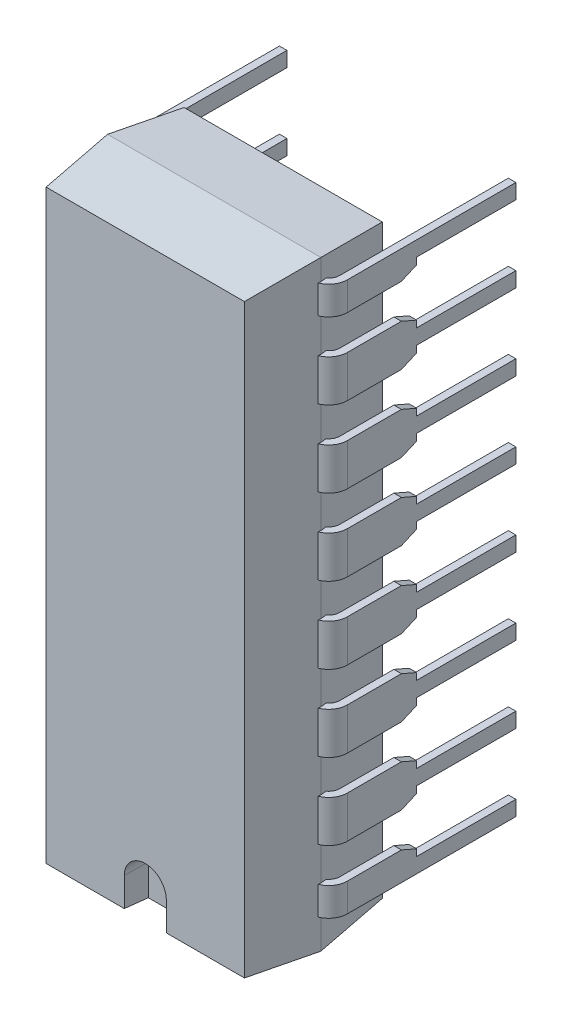
SolidWorks part; units mm, degrees
ref_plane "Plane1" through (0, 0, 0) normal (0, 0, 1) x (1, 0, 0)
ref_plane "Plane2" through (0, 0, 0) normal (0, 1, 0) x (1, 0, 0)
ref_plane "Plane3" through (0, 0, 0) normal (1, 0, 0) x (0, 0, -1)
sketch "Sketch1" plane through (0, 0, 0) normal (0, 1, 0) x (1, 0, 0)
  line L0 (-3.3, -5.1) -> (-3.55, -2.805)
  line L1 (-3.55, -2.805) -> (3.55, -2.805) construction
  line L2 (3.55, -2.805) -> (3.3, -5.1)
  line L3 (3.3, -5.1) -> (-3.3, -5.1)
  line L4 (-3.55, -2.805) -> (-3.3, -0.51)
  line L5 (-3.3, -0.51) -> (3.3, -0.51)
  line L6 (3.3, -0.51) -> (3.55, -2.805)
  line L7 (0, 0) -> (3.3, 0) construction
  line L8 (0, -0.51) -> (0, -5.1) construction
  point P11 (0, -2.805)
  point P12 (0, -5.1)
  point P13 (0, -0.51)
  dimension "D1" = 0.51
  dimension "F" = 7.1
  dimension "D2" = 5.1
  dimension "D4" = 6.6
extrude "Basic Shape" add sketch "Sketch1" along normal mid plane 20
sketch "Sketch2" plane through (0, 0, 0) normal (1, 0, 0) x (0, 0, -1)
  line L1 (-0.51, -10) -> (-2.805, -10) construction
  line L2 (-0.51, 10) -> (-0.51, -10) construction
  line L3 (-0.51, 10) -> (-0.51, 9.75)
  line L4 (-0.51, 10) -> (-2.805, 10) construction
  line L5 (-0.51, 10) -> (-2.805, 10)
  line L6 (-2.805, 10) -> (-0.51, 9.75)
  line L7 (-0.51, -10) -> (-2.805, -10)
  line L9 (-2.805, -10) -> (-0.51, -9.75)
  line L11 (-0.51, -9.75) -> (-0.51, -10)
  dimension "D1" = 0.25
extrude "Side Profile1" cut sketch "Sketch2" against normal through all and the other way through all
sketch "Sketch3" plane through (0, 0, 0) normal (1, 0, 0) x (0, 0, -1)
  line L0 (-2.805, 10) -> (-5.1, 10) construction
  line L1 (-2.805, 10) -> (-5.1, 10)
  line L2 (-5.1, 10) -> (-5.1, -10) construction
  line L3 (-5.1, 10) -> (-5.1, 9.75)
  line L4 (-2.805, 10) -> (-5.1, 9.75)
  line L5 (-2.805, -10) -> (-5.1, -10) construction
  line L6 (-2.805, -10) -> (-5.1, -10)
  line L7 (-2.805, -10) -> (-5.1, -9.75)
  line L8 (-5.1, -9.75) -> (-5.1, -10)
extrude "Side Profile2" cut sketch "Sketch3" against normal through all and the other way through all
sketch "First Pin Location" plane through (0, 0, 0) normal (1, 0, 0) x (0, 0, -1)
  line L0 (-2.805, 10) -> (-2.805, -10) construction
  point P0 (-2.805, -10)
  point P1 (-2.805, -8.73)
  dimension "Z" = 1.27
ref_plane "First Pin Plane" through (0, -8.73, 0) normal (0, 1, 0) x (-1, 0, 0)
sketch "Sketch4" plane through (0, 0, 5.1) normal (0, 0, 1) x (1, 0, 0)
  line L2 (-0.7, -10) -> (-0.7, -8.8)
  line L3 (0.7, -8.8) -> (0.7, -10)
  line L4 (-3.55, -10) -> (3.55, -10) construction
  line L5 (-0.7, -10) -> (0.7, -10)
  arc A0 (-0.7, -8.8) -> (0.7, -8.8) centre (0, -8.8) cw
  dimension "D1" = 1.2
  dimension "D2" = 1.4
extrude "Location Mark" cut sketch "Sketch4" against normal blind 0.8
sketch "Sketch5" plane through (0, -8.73, 0) normal (0, 1, 0) x (1, 0, 0)
  line L0 (-3.55, -2.805) -> (3.55, -2.805) construction
  line L1 (0, -2.805) -> (3.31, -2.805)
  line L2 (3.81, -2.305) -> (3.81, 3.3)
  line L3 (3.81, -2.805) -> (-3.81, -2.805) construction
  arc A0 (3.81, -2.305) -> (3.31, -2.805) centre (3.31, -2.305) cw
  point P0 (-3.81, -2.805)
  point P8 (0, -2.805)
  dimension "D3" = 3.3
  dimension "D2" = 0.5
  dimension "D1" = 7.62
sketch "Sketch6" plane through (0, 0, 0) normal (1, 0, 0) x (0, 0, -1)
  line L0 (-2.93, -8.035) -> (-2.68, -8.035)
  line L1 (-2.93, -8.035) -> (-2.93, -9.425)
  line L2 (-2.68, -9.425) -> (-2.93, -9.425)
  line L3 (-2.68, -9.425) -> (-2.68, -8.035)
  line L4 (-2.68, -8.035) -> (-2.93, -9.425) construction
  point P4 (-2.805, -8.73)
  dimension "D1" = 1.39
  dimension "D2" = 0.25
sweep "First Pin" add profiles "Sketch6" path "Sketch5"
sketch "Sketch7" plane through (3.685, 0, 0) normal (-1, 0, 0) x (0, 0, 1)
  line L0 (-3.3, -9.425) -> (-3.3, -8.035) construction
  line L1 (-3.3, -8.035) -> (-3.3, -9.425) construction
  line L2 (-3.3, -8.98) -> (-3.3, -8.48) construction
  line L3 (-3.3, -8.98) -> (0, -8.98)
  line L4 (0.51, 9.75) -> (0.51, -9.75) construction
  line L5 (-3.3, -8.48) -> (0, -8.48)
  line L6 (0, -8.48) -> (0, -8.2575)
  line L7 (0, -8.98) -> (0, -9.2025)
  line L8 (2.305, -8.035) -> (-3.3, -8.035) construction
  line L9 (0.51, -8.035) -> (-3.3, -8.035)
  line L10 (2.305, -9.425) -> (-3.3, -9.425) construction
  line L11 (0.51, -9.425) -> (-3.3, -9.425)
  line L12 (-3.3, -8.98) -> (-3.3, -9.425)
  line L13 (-3.3, -8.035) -> (-3.3, -8.48)
  line L14 (0, -9.2025) -> (0.51, -9.425)
  line L16 (0, -8.2575) -> (0.51, -8.035)
  point P10 (-3.3, -8.2575)
  dimension "D1" = 0.5
extrude "Pin Relief" cut sketch "Sketch7" against normal through all
mirror "Opp Pin" about plane through (0, 0, 0) normal (1, 0, 0) of "Pin Relief", "First Pin"
pattern_linear "Remaining Pins" count 8 spacing 2.54 along (0, 1, 0) of "First Pin", "Opp Pin", "Pin Relief"
sketch "Sketch9" plane through (0, -9.425, 0) normal (0, -1, 0) x (1, 0, 0)
  line L0 (3.935, 0) -> (3.685, 0) construction
  line L1 (3.935, 0) -> (3.685, 0)
  line L2 (-3.935, 0) -> (-3.685, 0) construction
  line L3 (-3.935, 0) -> (-3.685, 0)
  line L7 (3.685, 2.305) -> (3.685, 0.51)
  line L8 (3.685, 0.51) -> (3.935, 0.51)
  line L9 (3.935, 0.51) -> (3.935, 2.305)
  line L11 (3.5412, 2.8857) -> (3.55, 2.805)
  line L12 (3.55, 2.805) -> (3.5287, 2.6096)
  line L14 (3.685, 2.305) -> (3.685, 0)
  line L16 (3.935, 0) -> (3.935, 2.305)
  line L18 (3.5412, 2.8857) -> (3.55, 2.805)
  line L19 (3.55, 2.805) -> (3.5287, 2.6096)
  line L22 (-3.685, 0.51) -> (-3.685, 2.305)
  line L24 (-3.5287, 2.6096) -> (-3.55, 2.805)
  line L25 (-3.55, 2.805) -> (-3.5412, 2.8857)
  line L27 (-3.935, 2.305) -> (-3.935, 0.51)
  line L28 (-3.935, 0.51) -> (-3.685, 0.51)
  line L29 (-3.685, 0) -> (-3.685, 2.305)
  line L31 (-3.5287, 2.6096) -> (-3.55, 2.805)
  line L32 (-3.55, 2.805) -> (-3.5412, 2.8857)
  line L34 (-3.935, 2.305) -> (-3.935, 0)
  arc A2 (3.935, 2.305) -> (3.5412, 2.8857) centre (3.31, 2.305) ccw
  arc A3 (3.935, 2.305) -> (3.5412, 2.8857) centre (3.31, 2.305) ccw
  arc A4 (3.685, 2.305) -> (3.5287, 2.6096) centre (3.31, 2.305) ccw
  arc A5 (3.685, 2.305) -> (3.5287, 2.6096) centre (3.31, 2.305) ccw
  arc A6 (-3.5287, 2.6096) -> (-3.685, 2.305) centre (-3.31, 2.305) ccw
  arc A7 (-3.5287, 2.6096) -> (-3.685, 2.305) centre (-3.31, 2.305) ccw
  arc A8 (-3.5412, 2.8857) -> (-3.935, 2.305) centre (-3.31, 2.305) ccw
  arc A9 (-3.5412, 2.8857) -> (-3.935, 2.305) centre (-3.31, 2.305) ccw
  dimension "D1" = 0
  dimension "D2" = 0
extrude "Pin Relief1" cut sketch "Sketch9" against normal up to surface (0.445 mm away) up to face at (-3.81, -8.98, -1.65)
sketch "Sketch10" plane through (0, 9.745, 0) normal (0, 1, 0) x (-1, 0, 0)
  line L0 (3.935, 0) -> (3.685, 0) construction
  line L1 (3.935, 0) -> (3.685, 0)
  line L2 (-3.935, 0) -> (-3.685, 0) construction
  line L3 (-3.935, 0) -> (-3.685, 0)
  line L7 (3.685, 0.51) -> (3.935, 0.51)
  line L8 (3.935, 0.51) -> (3.935, 2.305)
  line L10 (3.5412, 2.8857) -> (3.55, 2.805)
  line L11 (3.55, 2.805) -> (3.5287, 2.6096)
  line L13 (3.685, 2.305) -> (3.685, 0.51)
  line L14 (-3.935, 0.51) -> (-3.685, 0.51)
  line L15 (3.935, 0) -> (3.935, 2.305)
  line L16 (-3.685, 0.51) -> (-3.685, 2.305)
  line L17 (3.5412, 2.8857) -> (3.55, 2.805)
  line L18 (3.55, 2.805) -> (3.5287, 2.6096)
  line L19 (-3.5287, 2.6096) -> (-3.55, 2.805)
  line L20 (3.685, 2.305) -> (3.685, 0)
  line L21 (-3.55, 2.805) -> (-3.5412, 2.8857)
  line L22 (-3.935, 2.305) -> (-3.935, 0.51)
  line L24 (-3.685, 0) -> (-3.685, 2.305)
  line L25 (-3.5287, 2.6096) -> (-3.55, 2.805)
  line L26 (-3.55, 2.805) -> (-3.5412, 2.8857)
  line L27 (-3.935, 2.305) -> (-3.935, 0)
  arc A2 (3.935, 2.305) -> (3.5412, 2.8857) centre (3.31, 2.305) ccw
  arc A3 (3.935, 2.305) -> (3.5412, 2.8857) centre (3.31, 2.305) ccw
  arc A4 (3.685, 2.305) -> (3.5287, 2.6096) centre (3.31, 2.305) ccw
  arc A5 (3.685, 2.305) -> (3.5287, 2.6096) centre (3.31, 2.305) ccw
  arc A6 (-3.5287, 2.6096) -> (-3.685, 2.305) centre (-3.31, 2.305) ccw
  arc A7 (-3.5412, 2.8857) -> (-3.935, 2.305) centre (-3.31, 2.305) ccw
  arc A8 (-3.5287, 2.6096) -> (-3.685, 2.305) centre (-3.31, 2.305) ccw
  arc A9 (-3.5412, 2.8857) -> (-3.935, 2.305) centre (-3.31, 2.305) ccw
  dimension "D1" = 0
  dimension "D2" = 0
extrude "Pin Relief2" cut sketch "Sketch10" against normal up to surface (0.445 mm away) up to face at (-3.81, 9.3, -1.65)
sketch "Component_Outline" plane through (0, 0, 0) normal (0, 0, 1) x (1, 0, 0)
  line L0 (3.55, 10) -> (3.55, 9.3)
  line L1 (3.55, 9.3) -> (3.935, 9.3)
  line L2 (3.935, 9.3) -> (3.935, 8.355)
  line L3 (3.935, 8.355) -> (3.55, 8.355)
  line L4 (3.55, 8.355) -> (3.55, 7.205)
  line L5 (3.55, 7.205) -> (3.935, 7.205)
  line L6 (3.935, 7.205) -> (3.935, 5.815)
  line L7 (3.935, 5.815) -> (3.55, 5.815)
  line L8 (3.55, 5.815) -> (3.55, 4.665)
  line L9 (3.55, 4.665) -> (3.935, 4.665)
  line L10 (3.935, 4.665) -> (3.935, 3.275)
  line L11 (3.935, 3.275) -> (3.55, 3.275)
  line L12 (3.55, 3.275) -> (3.55, 2.125)
  line L13 (3.55, 2.125) -> (3.935, 2.125)
  line L14 (3.935, 2.125) -> (3.935, 0.735)
  line L15 (3.935, 0.735) -> (3.55, 0.735)
  line L16 (3.55, 0.735) -> (3.55, -0.415)
  line L17 (3.55, -0.415) -> (3.935, -0.415)
  line L18 (3.935, -0.415) -> (3.935, -1.805)
  line L19 (3.935, -1.805) -> (3.55, -1.805)
  line L20 (3.55, -1.805) -> (3.55, -2.955)
  line L21 (3.55, -2.955) -> (3.935, -2.955)
  line L22 (3.935, -2.955) -> (3.935, -4.345)
  line L23 (3.935, -4.345) -> (3.55, -4.345)
  line L24 (3.55, -4.345) -> (3.55, -5.495)
  line L25 (3.55, -5.495) -> (3.935, -5.495)
  line L26 (3.935, -5.495) -> (3.935, -6.885)
  line L27 (3.935, -6.885) -> (3.55, -6.885)
  line L28 (3.55, -6.885) -> (3.55, -8.035)
  line L29 (3.55, -8.035) -> (3.935, -8.035)
  line L30 (3.935, -8.035) -> (3.935, -8.98)
  line L31 (3.935, -8.98) -> (3.55, -8.98)
  line L32 (3.55, -8.98) -> (3.55, -10)
  line L33 (0, 10) -> (0, -10) construction
  line L34 (-3.55, 10) -> (3.55, 10) construction
  line L35 (-3.55, -10) -> (3.55, -10) construction
  line L36 (-3.55, -8.98) -> (-3.55, -10)
  line L37 (-3.935, -8.98) -> (-3.55, -8.98)
  line L38 (-3.935, -8.035) -> (-3.935, -8.98)
  line L39 (-3.55, -8.035) -> (-3.935, -8.035)
  line L40 (-3.55, -6.885) -> (-3.55, -8.035)
  line L41 (-3.935, -6.885) -> (-3.55, -6.885)
  line L42 (-3.935, -5.495) -> (-3.935, -6.885)
  line L43 (-3.55, -5.495) -> (-3.935, -5.495)
  line L44 (-3.55, -4.345) -> (-3.55, -5.495)
  line L45 (-3.935, -4.345) -> (-3.55, -4.345)
  line L46 (-3.935, -2.955) -> (-3.935, -4.345)
  line L47 (-3.55, -2.955) -> (-3.935, -2.955)
  line L48 (-3.55, -1.805) -> (-3.55, -2.955)
  line L49 (-3.935, -1.805) -> (-3.55, -1.805)
  line L50 (-3.935, -0.415) -> (-3.935, -1.805)
  line L51 (-3.55, -0.415) -> (-3.935, -0.415)
  line L52 (-3.55, 0.735) -> (-3.55, -0.415)
  line L53 (-3.935, 0.735) -> (-3.55, 0.735)
  line L54 (-3.935, 2.125) -> (-3.935, 0.735)
  line L55 (-3.55, 2.125) -> (-3.935, 2.125)
  line L56 (-3.55, 3.275) -> (-3.55, 2.125)
  line L57 (-3.935, 3.275) -> (-3.55, 3.275)
  line L58 (-3.935, 4.665) -> (-3.935, 3.275)
  line L59 (-3.55, 4.665) -> (-3.935, 4.665)
  line L60 (-3.55, 5.815) -> (-3.55, 4.665)
  line L61 (-3.935, 5.815) -> (-3.55, 5.815)
  line L62 (-3.935, 7.205) -> (-3.935, 5.815)
  line L63 (-3.55, 7.205) -> (-3.935, 7.205)
  line L64 (-3.55, 8.355) -> (-3.55, 7.205)
  line L65 (-3.935, 8.355) -> (-3.55, 8.355)
  line L66 (-3.935, 9.3) -> (-3.935, 8.355)
  line L67 (-3.55, 9.3) -> (-3.935, 9.3)
  line L68 (-3.55, 10) -> (-3.55, 9.3)
  line L69 (3.55, 10) -> (-3.55, 10)
  line L70 (-3.55, -10) -> (3.55, -10)
